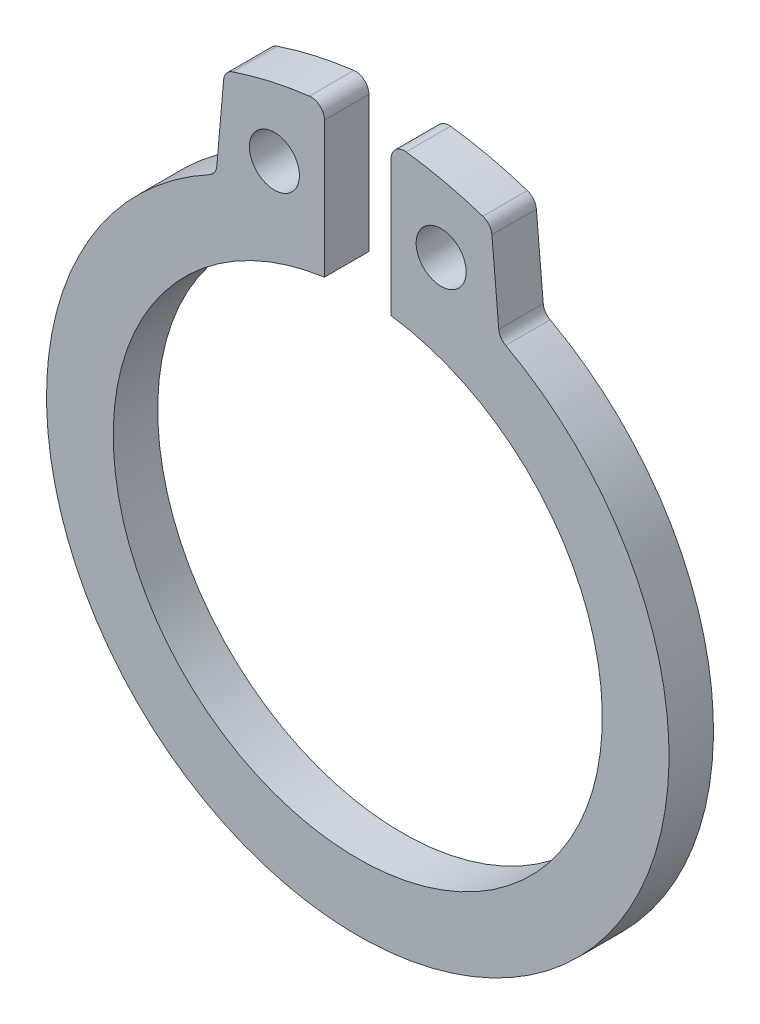
SolidWorks part; units mm, degrees
material "普通碳钢"
ref_plane "前视基准面" through (0, 0, 0) normal (0, 0, 1) x (1, 0, 0)
ref_plane "上视基准面" through (0, 0, 0) normal (0, 1, 0) x (1, 0, 0)
ref_plane "右视基准面" through (0, 0, 0) normal (1, 0, 0) x (0, 0, -1)
sketch "草图1" plane through (0, 0, 0) normal (0, 0, 1) x (1, 0, 0)
  line L0 (0, 3.5) -> (0, 0) construction
  line L1 (-0.75, 8.8433) -> (-0.75, 5.4486)
  line L2 (-3, 8.3526) -> (-3.1854, 6.2332)
  line L3 (3, 8.3526) -> (3.1854, 6.2332)
  line L4 (0.75, 8.8433) -> (0.75, 5.4486)
  line L5 (-1.5363, 7.1459) -> (1.5517, 7.1459) construction
  arc A0 (-0.75, 5.4486) -> (0.75, 5.4486) centre (0, 0) ccw
  arc A1 (-3.1854, 6.2332) -> (3.1854, 6.2332) centre (0, 0) ccw
  arc A2 (-0.75, 8.8433) -> (-3, 8.3526) centre (0, 0) ccw
  arc A3 (0.75, 8.8433) -> (3, 8.3526) centre (0, 0) cw
  circle A4 centre (0, 0) radius 7 construction
  circle A5 centre (0, 0) radius 5.5 construction
  circle A6 centre (-1.875, 7.1459) radius 0.5625
  circle A7 centre (1.875, 7.1459) radius 0.5625
  point P5 (2.2473, 0.6871)
  point P12 (1.291, 0.3947)
  point P18 (-0.75, 7.1459)
  dimension "D2" = 11
  dimension "D3" = 17.75
  dimension "D6" = 1.125
  dimension "D4" = 1.5
  dimension "D5" = 2.25
  dimension "D7" = 3.75
  dimension "D8" = 5
  dimension "D1" = 1.5
extrude "凸台-拉伸1" add sketch "草图1" along normal blind 1
fillet "圆角1" radius 0.3 2 edges at (3, 8.3526, 0.5) (-3, 8.3526, 0.5)
fillet "圆角2" radius 0.3 4 edges at (0.75, 8.8433, 0.5) (-0.75, 8.8433, 0.5) (3.1854, 6.2332, 0.5) (-3.1854, 6.2332, 0.5)
move or copy body "实体-移动/复制1" [suppressed] bodies to move or copy 106
equation "\"基本尺寸\"= 2.7"
equation "\"等距距离\"= 1"
equation "\"大圆尺寸\"= 7"
equation "\"孔定位\"= \"等距距离\" * 2.5"
equation "\"孔大小\"= \"等距距离\" * 0.75"
equation "\"间隙\"= \"等距距离\""
equation "\"头部宽度\"= \"等距距离\" * 1.5"
equation "\"s\"= 0.4"
equation "\"D2@草图1\"=\"基本尺寸\""
equation "\"D1@草图1\"=\"等距距离\""
equation "\"D3@草图1\"=\"大圆尺寸\""
equation "\"D7@草图1\"=\"孔定位\""
equation "\"D6@草图1\"=\"孔大小\""
equation "\"D4@草图1\"=\"间隙\""
equation "\"D5@草图1\"=\"头部宽度\""
equation "\"D1@凸台-拉伸1\"=\"s\""
